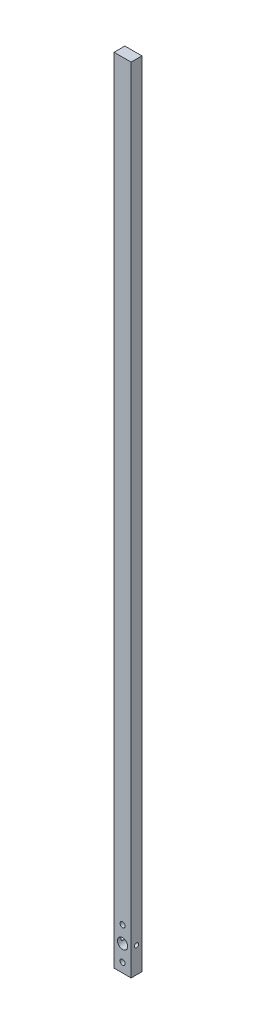
SolidWorks part; units mm, degrees
material "6061 Alloy"
ref_plane "Front Plane" through (0, 0, 0) normal (0, 0, 1) x (1, 0, 0)
ref_plane "Top Plane" through (0, 0, 0) normal (0, 1, 0) x (1, 0, 0)
ref_plane "Right Plane" through (0, 0, 0) normal (1, 0, 0) x (0, 0, -1)
sketch "Sketch1" plane through (0, 0, 0) normal (0, 0, 1) x (1, 0, 0)
  line L1 (-5, 450) -> (5, 450)
  line L2 (-5, 450) -> (-5, -15)
  line L3 (-5, -15) -> (5, -15)
  line L4 (5, 450) -> (5, -15)
  circle A0 centre (0, -9.5) radius 1.5
  circle A1 centre (0, 0) radius 3
  circle A2 centre (0, 9.5) radius 1.5
  dimension "D1" = 450
  dimension "D6" = 3
  dimension "D7" = 6
  dimension "D8" = 3
  dimension "D2" = 10
  dimension "D3" = 9.5
  dimension "D4" = 9.5
  dimension "D5" = 15
  dimension "D9" = 5
  dimension "D10" = 19
extrude "Boss-Extrude1" add sketch "Sketch1" along normal blind 6.35
hole_wizard "Tap Drill for M3x0.5 Tap1" positions "Sketch2" profile "Sketch3" hole size "M3x0.5" standard "ANSI Metric" end condition through all
sketch "Sketch2" plane through (5, 0, 0) normal (1, 0, 0) x (0, 0, -1)
  point P0 (-3.175, 0)
sketch "Sketch3" plane through (5, 0, 3.175) normal (0, 1, 0) x (0, 0, -1)
  line L0 (0, 0) -> (0, 10)
  line L1 (0, 10) -> (1.25, 10)
  line L2 (1.25, 10) -> (1.25, 0)
  line L5 (1.25, 0) -> (0, 0)
  line L11 (0, -6.35) -> (0, 107.95) construction
  dimension "Thru Hole Dia." = 2.5
  dimension "Thru Hole Depth" = 10
